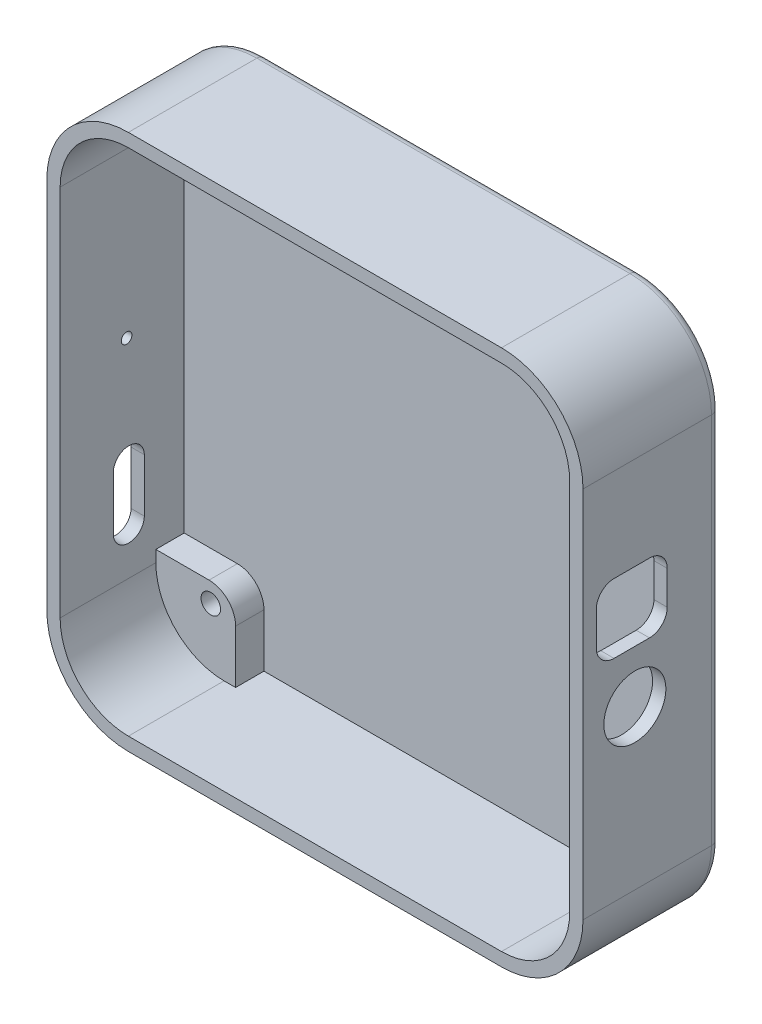
SolidWorks part; units mm, degrees
ref_plane "前视基准面" through (0, 0, 0) normal (0, 0, 1) x (1, 0, 0)
ref_plane "上视基准面" through (0, 0, 0) normal (0, 1, 0) x (1, 0, 0)
ref_plane "右视基准面" through (0, 0, 0) normal (1, 0, 0) x (0, 0, -1)
sketch "草图1" plane through (0, 0, 0) normal (0, 0, 1) x (1, 0, 0)
  line L1 (-3.1468, 60.5) -> (38.9532, 60.5)
  line L2 (-12.3468, 51.3) -> (-12.3468, 9.2)
  line L3 (-3.1468, 0) -> (38.9532, 0)
  line L4 (48.1532, 51.3) -> (48.1532, 9.2)
  arc A0 (38.9532, 60.5) -> (48.1532, 51.3) centre (38.9532, 51.3) cw
  arc A1 (48.1532, 9.2) -> (38.9532, 0) centre (38.9532, 9.2) cw
  arc A2 (-3.1468, 0) -> (-12.3468, 9.2) centre (-3.1468, 9.2) cw
  arc A3 (-12.3468, 51.3) -> (-3.1468, 60.5) centre (-3.1468, 51.3) cw
  point P6 (48.1532, 60.5)
  point P9 (48.1532, 0)
  point P12 (-12.3468, 0)
  dimension "D3" = 9.2
  dimension "D1" = 60.5
  dimension "D2" = 60.5
extrude "凸台-拉伸1" add sketch "草图1" along normal blind 1.5
sketch "草图3" plane through (0, 0, 1.5) normal (0, 0, 1) x (1, 0, 0)
  line L4 (38.9532, 59) -> (-3.1468, 59)
  line L5 (-10.8468, 51.3) -> (-10.8468, 9.2)
  line L6 (-3.1468, 1.5) -> (38.9532, 1.5)
  line L7 (46.6532, 9.2) -> (46.6532, 51.3)
  line L8 (38.9532, 60.5) -> (-3.1468, 60.5)
  line L9 (-12.3468, 51.3) -> (-12.3468, 9.2)
  line L10 (-3.1468, 0) -> (38.9532, 0)
  line L11 (48.1532, 9.2) -> (48.1532, 51.3)
  line L12 (38.9532, 60.5) -> (-3.1468, 60.5)
  line L13 (-12.3468, 51.3) -> (-12.3468, 9.2)
  line L14 (-3.1468, 0) -> (38.9532, 0)
  line L15 (48.1532, 9.2) -> (48.1532, 51.3)
  arc A4 (46.6532, 51.3) -> (38.9532, 59) centre (38.9532, 51.3) ccw
  arc A5 (-3.1468, 59) -> (-10.8468, 51.3) centre (-3.1468, 51.3) ccw
  arc A6 (-10.8468, 9.2) -> (-3.1468, 1.5) centre (-3.1468, 9.2) ccw
  arc A7 (38.9532, 1.5) -> (46.6532, 9.2) centre (38.9532, 9.2) ccw
  arc A8 (48.1532, 51.3) -> (38.9532, 60.5) centre (38.9532, 51.3) ccw
  arc A9 (-3.1468, 60.5) -> (-12.3468, 51.3) centre (-3.1468, 51.3) ccw
  arc A10 (-12.3468, 9.2) -> (-3.1468, 0) centre (-3.1468, 9.2) ccw
  arc A11 (38.9532, 0) -> (48.1532, 9.2) centre (38.9532, 9.2) ccw
  arc A12 (48.1532, 51.3) -> (38.9532, 60.5) centre (38.9532, 51.3) ccw
  arc A13 (-3.1468, 60.5) -> (-12.3468, 51.3) centre (-3.1468, 51.3) ccw
  arc A14 (-12.3468, 9.2) -> (-3.1468, 0) centre (-3.1468, 9.2) ccw
  arc A15 (38.9532, 0) -> (48.1532, 9.2) centre (38.9532, 9.2) ccw
  dimension "D1" = 0
  dimension "D2" = 1.5
extrude "凸台-拉伸3" add sketch "草图3" along normal blind 14
sketch "草图4" plane through (0, 0, 1.5) normal (0, 0, 1) x (1, 0, 0)
  line L0 (0, 59) -> (0, 52)
  line L1 (38.9532, 59) -> (-3.1468, 59) construction
  line L2 (-3, 49) -> (-10.8468, 49)
  line L3 (-10.8468, 51.3) -> (-10.8468, 9.2) construction
  circle A0 centre (-4.6468, 52.8) radius 1.1
  arc A1 (0, 52) -> (-3, 49) centre (-3, 52) cw
  point P13 (0, 49)
  line M6 (38.9532, 59) -> (-3.1468, 59)
  arc M7 (-3.1468, 59) -> (-10.8468, 51.3) centre (-3.1468, 51.3) ccw
  line M8 (-10.8468, 51.3) -> (-10.8468, 9.2)
  dimension "D1" = 2.2
  dimension "D6" = 3
  dimension "D2" = 10
  dimension "D3" = 10.8468
  dimension "D4" = 6.2
  dimension "D5" = 6.2
extrude "凸台-拉伸4" add sketch "草图4" along normal blind 3.2 contours A1 L0 L2 A0 M6 M7 M8
sketch "草图5" plane through (0, 0, 1.5) normal (0, 0, 1) x (1, 0, 0)
  line L0 (-10.8468, 10.5) -> (-4.8468, 10.5)
  line L1 (-10.8468, 51.3) -> (-10.8468, 9.2) construction
  line L2 (-1.8468, 7.5) -> (-1.8468, 1.5)
  line L3 (-3.1468, 1.5) -> (38.9532, 1.5) construction
  line L4 (-10.8468, 49) -> (-10.8468, 9.2) construction
  circle A0 centre (-4.6468, 8.3) radius 1.1
  arc A1 (-1.8468, 7.5) -> (-4.8468, 10.5) centre (-4.8468, 7.5) ccw
  point P13 (-1.8468, 10.5)
  line M8 (-10.8468, 49) -> (-10.8468, 9.2)
  arc M9 (-10.8468, 9.2) -> (-3.1468, 1.5) centre (-3.1468, 9.2) ccw
  line M10 (-3.1468, 1.5) -> (38.9532, 1.5)
  dimension "D1" = 2.2
  dimension "D6" = 3
  dimension "D2" = 9
  dimension "D3" = 9
  dimension "D4" = 6.8
  dimension "D5" = 6.2
extrude "凸台-拉伸5" add sketch "草图5" along normal blind 3.2 contours L2 A1 L0 A0 M8 M9 M10
sketch "草图8" plane through (0, 0, 1.5) normal (0, 0, 1) x (1, 0, 0)
  line L0 (37.6532, 1.5) -> (37.6532, 7.5)
  line L1 (-3.1468, 1.5) -> (38.9532, 1.5) construction
  line L2 (40.6532, 10.5) -> (46.6532, 10.5)
  line L3 (46.6532, 9.2) -> (46.6532, 51.3) construction
  line L4 (46.6532, 9.2) -> (46.6532, 51.3) construction
  line L13 (-1.8468, 7.5) -> (-1.8468, 1.5)
  line L14 (-1.8468, 1.5) -> (38.9532, 1.5)
  line L15 (46.6532, 9.2) -> (46.6532, 51.3)
  line L16 (38.9532, 59) -> (0, 59)
  line L17 (0, 59) -> (0, 52)
  line L18 (-3, 49) -> (-10.8468, 49)
  line L19 (-10.8468, 49) -> (-10.8468, 10.5)
  line L20 (-10.8468, 10.5) -> (-4.8468, 10.5)
  line L21 (-1.8468, 7.5) -> (-1.8468, 1.5)
  line L22 (-1.8468, 1.5) -> (38.9532, 1.5)
  line L23 (46.6532, 9.2) -> (46.6532, 51.3)
  line L24 (38.9532, 59) -> (0, 59)
  line L25 (0, 59) -> (0, 52)
  line L26 (-3, 49) -> (-10.8468, 49)
  line L27 (-10.8468, 49) -> (-10.8468, 10.5)
  line L28 (-10.8468, 10.5) -> (-4.8468, 10.5)
  circle A0 centre (40.4532, 8.3) radius 1.1
  arc A1 (37.6532, 7.5) -> (40.6532, 10.5) centre (40.6532, 7.5) cw
  arc A6 (-1.8468, 7.5) -> (-4.8468, 10.5) centre (-4.8468, 7.5) ccw
  arc A7 (38.9532, 1.5) -> (46.6532, 9.2) centre (38.9532, 9.2) ccw
  arc A8 (46.6532, 51.3) -> (38.9532, 59) centre (38.9532, 51.3) ccw
  arc A9 (-3, 49) -> (0, 52) centre (-3, 52) ccw
  arc A10 (-1.8468, 7.5) -> (-4.8468, 10.5) centre (-4.8468, 7.5) ccw
  arc A11 (38.9532, 1.5) -> (46.6532, 9.2) centre (38.9532, 9.2) ccw
  arc A12 (46.6532, 51.3) -> (38.9532, 59) centre (38.9532, 51.3) ccw
  arc A13 (-3, 49) -> (0, 52) centre (-3, 52) ccw
  point P13 (37.6532, 10.5)
  line M6 (-1.8468, 1.5) -> (38.9532, 1.5)
  arc M7 (38.9532, 1.5) -> (46.6532, 9.2) centre (38.9532, 9.2) ccw
  line M8 (46.6532, 9.2) -> (46.6532, 51.3)
  dimension "D1" = 2.2
  dimension "D6" = 3
  dimension "D2" = 9
  dimension "D3" = 9
  dimension "D4" = 6.8
  dimension "D5" = 6.2
  dimension "D7" = 0
extrude "凸台-拉伸7" add sketch "草图8" along normal blind 3.2 contours A1 L0 L2 A0 M6 M7 M8
sketch "草图9" plane through (-12.3468, 0, 0) normal (-1, 0, 0) x (0, 0, 1)
  line L1 (15.5, 51.3) -> (0, 51.3) construction
  line L6 (0, 51.3) -> (0, 9.2)
  line L7 (0, 9.2) -> (15.5, 9.2)
  line L8 (15.5, 9.2) -> (15.5, 51.3)
  line L9 (15.5, 51.3) -> (0, 51.3)
  line L10 (0, 51.3) -> (0, 9.2)
  line L11 (0, 9.2) -> (15.5, 9.2)
  line L12 (15.5, 9.2) -> (15.5, 51.3)
  line L13 (15.5, 51.3) -> (0, 51.3)
  circle A0 centre (8, 32.8) radius 0.6
  dimension "D1" = 1.2
  dimension "D2" = 8
  dimension "D3" = 18.5
  dimension "D4" = 0
extrude "切除-拉伸5" cut sketch "草图9" against normal up to surface (1.5 mm away) contours A0 up to face at (-10.8468, 30, 6.6)
sketch "草图10" plane through (-12.3468, 0, 0) normal (-1, 0, 0) x (0, 0, 1)
  line L0 (4.7, 59) -> (4.7, 1.5) construction
  line L1 (7.75, 20.4) -> (7.75, 14.4) construction
  line L2 (9.5, 20.4) -> (9.5, 14.4)
  line L3 (6, 20.4) -> (6, 14.4)
  line L8 (0, 51.3) -> (0, 9.2)
  line L9 (0, 9.2) -> (15.5, 9.2)
  line L10 (15.5, 9.2) -> (15.5, 51.3)
  line L11 (15.5, 51.3) -> (0, 51.3)
  line L12 (0, 51.3) -> (0, 9.2)
  line L13 (0, 9.2) -> (15.5, 9.2)
  line L14 (15.5, 9.2) -> (15.5, 51.3)
  line L15 (15.5, 51.3) -> (0, 51.3)
  arc A0 (9.5, 20.4) -> (6, 20.4) centre (7.75, 20.4) ccw
  arc A1 (6, 14.4) -> (9.5, 14.4) centre (7.75, 14.4) ccw
  point P6 (7.75, 17.4)
  dimension "D1" = 6
  dimension "D2" = 1.3
  dimension "3.5" = 3.5
  dimension "D4" = 8.2
  dimension "D3" = 0
extrude "切除-拉伸6" cut sketch "草图10" against normal up to surface (1.5 mm away) contours L3 A1 L2 A0 up to face at (-10.8468, 33.4, 8)
sketch "草图16" plane through (48.1532, 0, 0) normal (1, 0, 0) x (0, 0, -1)
  line L0 (-15.5, 51.3) -> (0, 51.3) construction
  line L1 (-12, 40.8) -> (-8, 40.8)
  line L2 (-14, 38.8) -> (-14, 35)
  line L3 (-12, 33) -> (-8, 33)
  line L4 (-6, 38.8) -> (-6, 35)
  line L5 (0, 9.2) -> (0, 51.3) construction
  arc A0 (-14, 38.8) -> (-12, 40.8) centre (-12, 38.8) cw
  arc A1 (-8, 40.8) -> (-6, 38.8) centre (-8, 38.8) cw
  arc A2 (-6, 35) -> (-8, 33) centre (-8, 35) cw
  arc A3 (-12, 33) -> (-14, 35) centre (-12, 35) cw
  circle A4 centre (-9.65, 27.1) radius 3.5
  point P10 (-14, 40.8)
  point P15 (-6, 33)
  point P18 (-14, 33)
  dimension "D5" = 2
  dimension "D6" = 7
  dimension "D7" = 9.65
  dimension "D8" = 5.9
  dimension "D1" = 8
  dimension "D2" = 7.8
  dimension "D3" = 10.5
  dimension "D4" = 6
extrude "切除-拉伸7" cut sketch "草图16" against normal up to next
fillet "圆角1" radius 1 8 edges at (17.9032, 60.5, 0) (-9.6522, 57.8054, 0) (-12.3468, 30.25, 0) (-9.6522, 2.6946, 0) (17.9032, 0, 0) (45.4585, 2.6946, 0) (48.1532, 30.25, 0) (45.4585, 57.8054, 0)
